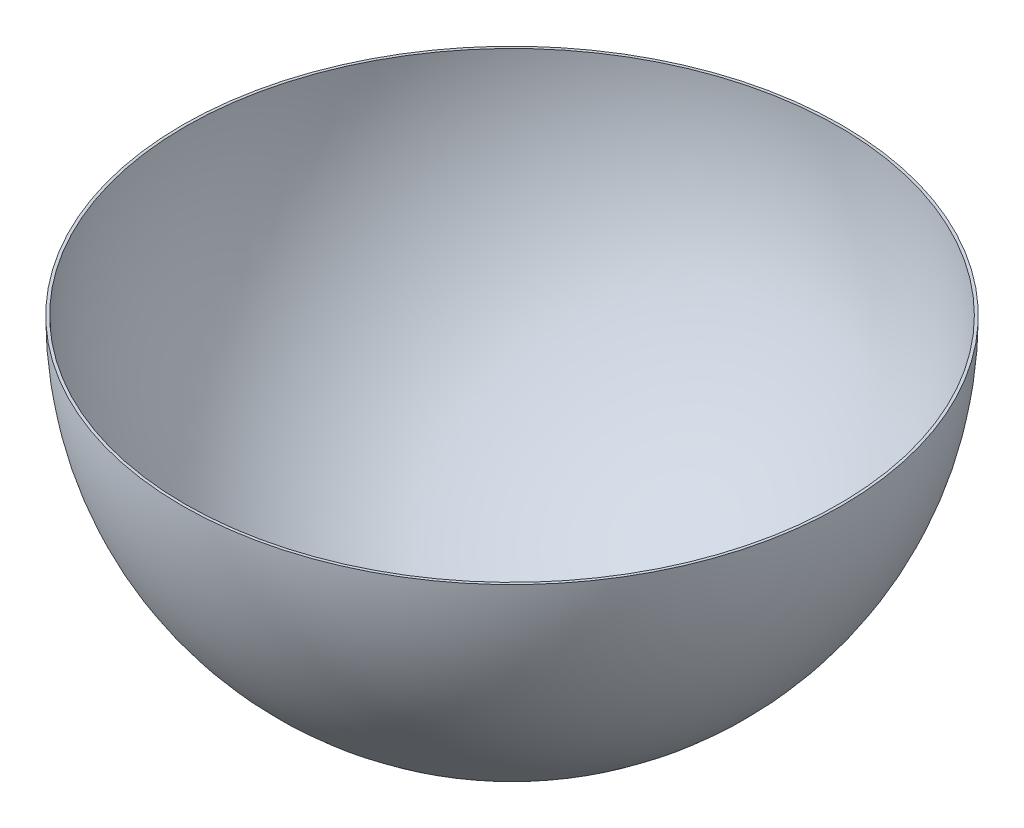
SolidWorks part; units mm, degrees
material "Duranickel(R) 301"
ref_plane "Front Plane" through (0, 0, 0) normal (0, 0, 1) x (1, 0, 0)
ref_plane "Top Plane" through (0, 0, 0) normal (0, 1, 0) x (1, 0, 0)
ref_plane "Right Plane" through (0, 0, 0) normal (1, 0, 0) x (0, 0, -1)
sketch "Sketch1" plane through (0, 0, 0) normal (0, 1, 0) x (1, 0, 0)
  line L0 (0, -226.695) -> (0, 226.695) construction
  line L1 (0, 226.695) -> (0, 228.6)
  line L2 (0, -226.695) -> (0, -228.6)
  arc A0 (0, 226.695) -> (0, -226.695) centre (0, 0) cw
  arc A1 (0, 228.6) -> (0, -228.6) centre (0, 0) cw
  dimension "D1" = 453.39
  dimension "D2" = 226.695
  dimension "D3" = 1.905
  dimension "D4" = 1.905
revolve "Revolve1" add sketch "Sketch1" angle 180 about L0
ref_plane "Plane1" through (0, -228.6, 0) normal (0, -1, 0) x (-1, 0, 0)
sketch "Sketch2" plane through (0, -228.6, 0) normal (0, -1, 0) x (-1, 0, 0)
  circle A0 centre (0, 0) radius 6.35
  dimension "D1" = 12.7
extrude "Cut-Extrude1" cut sketch "Sketch2" against normal through all
